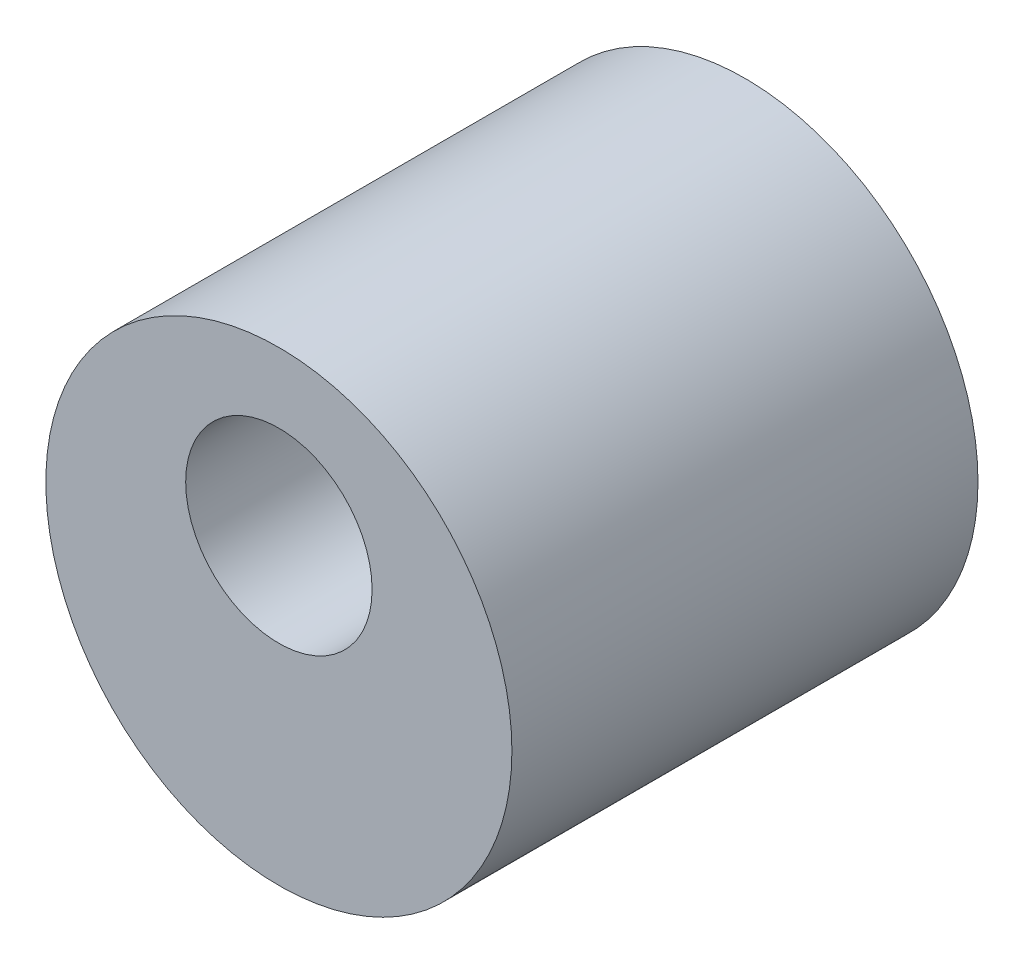
SolidWorks part; units mm, degrees
ref_plane "Alzado" through (0, 0, 0) normal (0, 0, 1) x (1, 0, 0)
ref_plane "Planta" through (0, 0, 0) normal (0, 1, 0) x (1, 0, 0)
ref_plane "Vista lateral" through (0, 0, 0) normal (1, 0, 0) x (0, 0, -1)
sketch "Croquis1" plane through (0, 0, 0) normal (0, 0, 1) x (1, 0, 0)
  circle A0 centre (0, 0) radius 5
  dimension "D1" = 10
extrude "Saliente-Extruir1" add sketch "Croquis1" along normal mid plane 10
sketch "Croquis2" plane through (0, 0, 5) normal (0, 0, 1) x (1, 0, 0)
  circle A0 centre (0, 1.5) radius 2
  dimension "D1" = 4
  dimension "D2" = 1.5
extrude "Cortar-Extruir1" cut sketch "Croquis2" against normal through all
